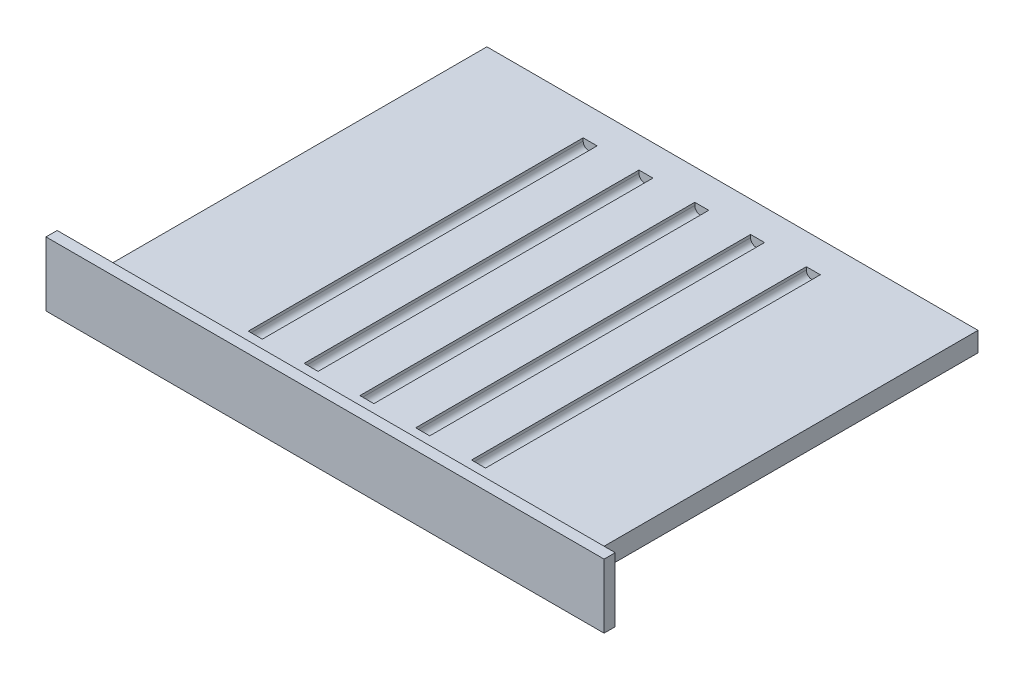
SolidWorks part; units mm, degrees
ref_plane "Front Plane" through (0, 0, 0) normal (0, 0, 1) x (1, 0, 0)
ref_plane "Top Plane" through (0, 0, 0) normal (0, 1, 0) x (1, 0, 0)
ref_plane "Right Plane" through (0, 0, 0) normal (1, 0, 0) x (0, 0, -1)
sketch "Sketch1" plane through (0, 0, 0) normal (0, 1, 0) x (1, 0, 0)
  line L1 (-68.6352, 33.5537) -> (107.3648, 33.5537)
  line L2 (-68.6352, 33.5537) -> (-68.6352, -108.4463)
  line L3 (-68.6352, -108.4463) -> (107.3648, -108.4463)
  line L4 (107.3648, 33.5537) -> (107.3648, -108.4463)
  dimension "D1" = 176
  dimension "D2" = 142
extrude "Boss-Extrude1" add sketch "Sketch1" along normal blind 7
sketch "Sketch2" plane through (0, 0, 108.4463) normal (0, 0, 1) x (1, 0, 0)
  line L0 (19.3648, 0) -> (19.3648, 7) construction
  line L1 (-68.6352, 0) -> (107.3648, 0) construction
  line L2 (-68.6352, 7) -> (107.3648, 7) construction
  line L3 (107.3648, 7) -> (107.3648, 0) construction
  line L4 (-76.6352, 15) -> (115.3648, 15)
  line L5 (-76.6352, 15) -> (-76.6352, -8)
  line L6 (-76.6352, -8) -> (115.3648, -8)
  line L7 (115.3648, 15) -> (115.3648, -8)
  line L8 (-76.6352, 15) -> (115.3648, -8) construction
  line L9 (-76.6352, -8) -> (115.3648, 15) construction
  point P6 (19.3648, 3.5)
  dimension "D1" = 8
  dimension "D2" = 8
extrude "Boss-Extrude2" add sketch "Sketch2" along normal blind 4
sketch "Sketch3" plane through (0, 0, 0) normal (0, -1, 0) x (1, 0, 0)
  line L0 (107.3648, 37.4463) -> (-68.6352, 37.4463) construction
  line L1 (107.3648, 108.4463) -> (107.3648, -33.5537) construction
  line L2 (-68.6352, -33.5537) -> (-68.6352, 108.4463) construction
  line L3 (107.3648, -33.5537) -> (-68.6352, -33.5537) construction
  line L4 (92.3648, 93.4463) -> (-53.6352, 93.4463)
  line L5 (92.3648, 93.4463) -> (92.3648, -18.5537)
  line L6 (92.3648, -18.5537) -> (-53.6352, -18.5537)
  line L7 (-53.6352, 93.4463) -> (-53.6352, -18.5537)
  line L8 (92.3648, 93.4463) -> (-53.6352, -18.5537) construction
  line L9 (92.3648, -18.5537) -> (-53.6352, 93.4463) construction
  point P6 (19.3648, 37.4463)
  dimension "D1" = 15
  dimension "D2" = 15
extrude "Cut-Extrude1" cut sketch "Sketch3" against normal blind 3
sketch "Sketch4" plane through (0, 7, 0) normal (0, 1, 0) x (1, 0, 0)
  line L0 (19.3648, 33.5537) -> (19.3648, -108.4463) construction
  line L1 (107.3648, 33.5537) -> (-68.6352, 33.5537) construction
  line L2 (-68.6352, -108.4463) -> (107.3648, -108.4463) construction
  line L3 (29.3648, 33.5537) -> (29.3648, -108.4463) construction
  line L4 (16.8648, 22.5537) -> (21.8648, 22.5537)
  line L5 (16.8648, 22.5537) -> (16.8648, -97.4463)
  line L6 (16.8648, -97.4463) -> (21.8648, -97.4463)
  line L7 (21.8648, 22.5537) -> (21.8648, -97.4463)
  line L8 (16.8648, 22.5537) -> (21.8648, -97.4463) construction
  line L9 (16.8648, -97.4463) -> (21.8648, 22.5537) construction
  line L10 (41.8648, -97.4463) -> (36.8648, -97.4463)
  line L11 (36.8648, 22.5537) -> (36.8648, -97.4463)
  line L12 (41.8648, 22.5537) -> (36.8648, 22.5537)
  line L13 (41.8648, 22.5537) -> (41.8648, -97.4463)
  line L14 (-3.1352, -97.4463) -> (1.8648, -97.4463)
  line L15 (-3.1352, 22.5537) -> (-3.1352, -97.4463)
  line L16 (1.8648, 22.5537) -> (1.8648, -97.4463)
  line L17 (-3.1352, 22.5537) -> (1.8648, 22.5537)
  line L18 (61.8648, 22.5537) -> (56.8648, 22.5537)
  line L19 (61.8648, -97.4463) -> (56.8648, -97.4463)
  line L20 (61.8648, 22.5537) -> (61.8648, -97.4463)
  line L21 (56.8648, 22.5537) -> (56.8648, -97.4463)
  line L22 (-23.1352, -97.4463) -> (-18.1352, -97.4463)
  line L23 (-23.1352, 22.5537) -> (-23.1352, -97.4463)
  line L24 (-18.1352, 22.5537) -> (-18.1352, -97.4463)
  line L25 (-23.1352, 22.5537) -> (-18.1352, 22.5537)
  point P6 (19.3648, -37.4463)
  dimension "D1" = 120
  dimension "D2" = 5
  dimension "D3" = 10
extrude "Cut-Extrude2" cut sketch "Sketch4" against normal blind 3
fillet "Fillet1" radius 2 10 edges at (-18.1352, 4, 37.4463) (1.8648, 4, 37.4463) (21.8648, 4, 37.4463) (-23.1352, 4, 37.4463) (-3.1352, 4, 37.4463) (16.8648, 4, 37.4463) (36.8648, 4, 37.4463) (41.8648, 4, 37.4463) (56.8648, 4, 37.4463) (61.8648, 4, 37.4463)
sketch "Sketch5" plane through (0, 0, 112.4463) normal (0, 0, 1) x (1, 0, 0)
  line L0 (-76.6352, 3.5) -> (115.3648, 3.5) construction
  line L1 (-76.6352, 15) -> (-76.6352, -8) construction
  line L2 (115.3648, -8) -> (115.3648, 15) construction
  line L3 (19.3648, 15) -> (19.3648, -8) construction
  line L4 (115.3648, 15) -> (-76.6352, 15) construction
  line L5 (-76.6352, -8) -> (115.3648, -8) construction
  circle A0 centre (-75.6352, 3.5) radius 3
  circle A1 centre (114.3648, 3.5) radius 3
  dimension "D2" = 6
  dimension "6" = 6
  dimension "D1" = 95
  dimension "D3" = 95
sketch "Sketch6" plane through (-76.6352, 0, 0) normal (-1, 0, 0) x (0, 0, 1)
  line L8 (108.4463, 15) -> (108.4463, -8)
  line L9 (108.4463, -8) -> (112.4463, -8)
  line L10 (112.4463, -8) -> (112.4463, 15)
  line L11 (112.4463, 15) -> (108.4463, 15)
  line L12 (108.4463, 15) -> (108.4463, -8)
  line L13 (108.4463, -8) -> (112.4463, -8)
  line L14 (112.4463, -8) -> (112.4463, 15)
  line L15 (112.4463, 15) -> (108.4463, 15)
  dimension "D1" = 0
extrude "Boss-Extrude3" add sketch "Sketch6" along normal blind 4
sketch "Sketch7" plane through (115.3648, 0, 0) normal (1, 0, 0) x (0, 0, -1)
  line L8 (-108.4463, -8) -> (-108.4463, 15)
  line L9 (-108.4463, 15) -> (-112.4463, 15)
  line L10 (-112.4463, 15) -> (-112.4463, -8)
  line L11 (-112.4463, -8) -> (-108.4463, -8)
  line L12 (-108.4463, -8) -> (-108.4463, 15)
  line L13 (-108.4463, 15) -> (-112.4463, 15)
  line L14 (-112.4463, 15) -> (-112.4463, -8)
  line L15 (-112.4463, -8) -> (-108.4463, -8)
  dimension "D1" = 0
extrude "Boss-Extrude4" add sketch "Sketch7" along normal blind 4
extrude "Cut-Extrude3" cut sketch "Sketch5" against normal through all
sketch "Sketch8" plane through (0, 0, 112.4463) normal (0, 0, 1) x (1, 0, 0)
  circle A0 centre (-75.6352, 3.5) radius 3
  circle A1 centre (114.3648, 3.5) radius 3
extrude "Boss-Extrude5" add sketch "Sketch8" against normal blind 2
equation "\"lent\"= 200"
equation "\"width\"= 145"
equation "\"thickness_01\"= 3"
equation "\"hight\"= 50"
equation "\"hole len\"= 180"
equation "\"hole width\"= 10"
equation "\"gap\"= 15"
equation "\"bottom dis\"= 7"
equation "\"support\"= 25"
equation "\"D1@Sketch1\"=\"hole len\"-4"
equation "\"D1@Boss-Extrude1\"=\"hole width\"-3"
equation "\"D1@Cut-Extrude1\"=\"hole width\"-7"
equation "\"D2@Sketch1\"=\"width\"-3"
